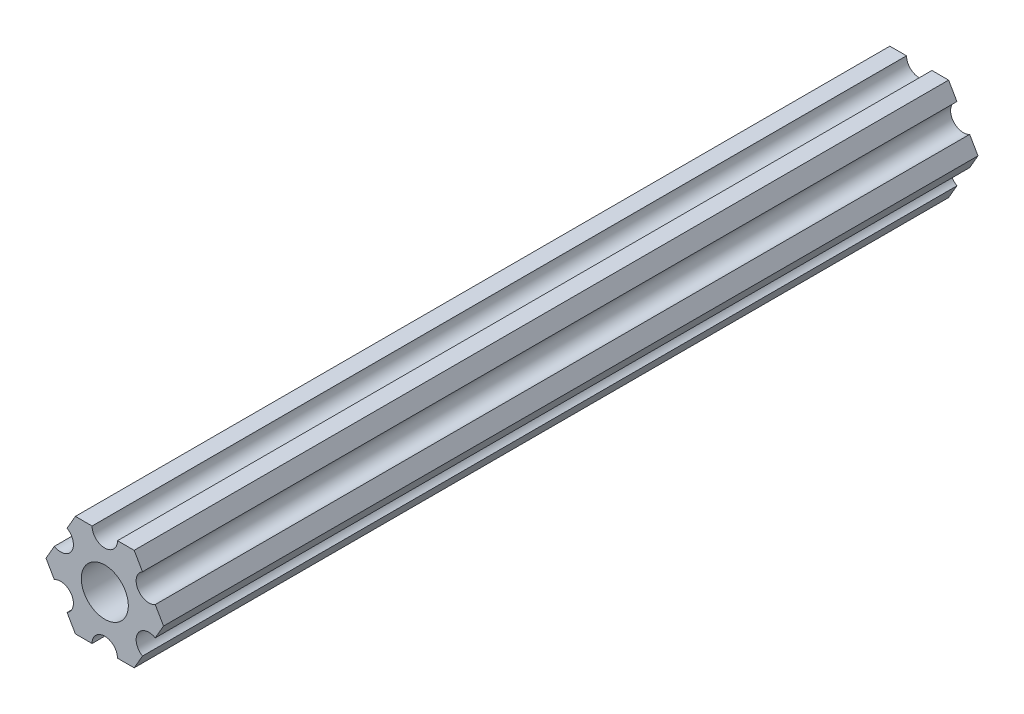
SolidWorks part; units mm, degrees
material "6061 Alloy"
ref_plane "Front Plane" through (0, 0, 0) normal (0, 0, 1) x (1, 0, 0)
ref_plane "Top Plane" through (0, 0, 0) normal (0, 1, 0) x (1, 0, 0)
ref_plane "Right Plane" through (0, 0, 0) normal (1, 0, 0) x (0, 0, -1)
ref_plane "Plane1" through (0, 0, 304.8) normal (0, 0, 1) x (1, 0, 0)
sketch "Sketch1" plane through (0, 0, 304.8) normal (0, 0, 1) x (1, 0, 0)
  line L0 (6.293, -1.8002) -> (7.3323, 0)
  line L1 (7.3323, 0) -> (6.293, 1.8002)
  line L2 (4.7055, 4.5498) -> (3.6662, 6.35)
  line L3 (3.6662, 6.35) -> (1.5875, 6.35)
  line L4 (-1.5875, 6.35) -> (-3.6662, 6.35)
  line L5 (-3.6662, 6.35) -> (-4.7055, 4.5498)
  line L6 (-6.293, 1.8002) -> (-7.3323, 0)
  line L7 (-7.3323, 0) -> (-6.293, -1.8002)
  line L8 (-4.7055, -4.5498) -> (-3.6662, -6.35)
  line L9 (-3.6662, -6.35) -> (-1.5875, -6.35)
  line L10 (1.5875, -6.35) -> (3.6662, -6.35)
  line L11 (3.6662, -6.35) -> (4.7055, -4.5498)
  arc A0 (6.293, 1.8002) -> (4.7055, 4.5498) centre (5.4993, 3.175) cw
  arc A1 (1.5875, 6.35) -> (-1.5875, 6.35) centre (0, 6.35) cw
  arc A2 (-4.7055, 4.5498) -> (-6.293, 1.8002) centre (-5.4993, 3.175) cw
  arc A3 (-6.293, -1.8002) -> (-4.7055, -4.5498) centre (-5.4993, -3.175) cw
  arc A4 (-1.5875, -6.35) -> (1.5875, -6.35) centre (0, -6.35) cw
  arc A5 (4.7055, -4.5498) -> (6.293, -1.8002) centre (5.4993, -3.175) cw
  circle A6 centre (0, 0) radius 2.9337
extrude "Boss-Extrude1" add sketch "Sketch1" against normal blind 101.6
